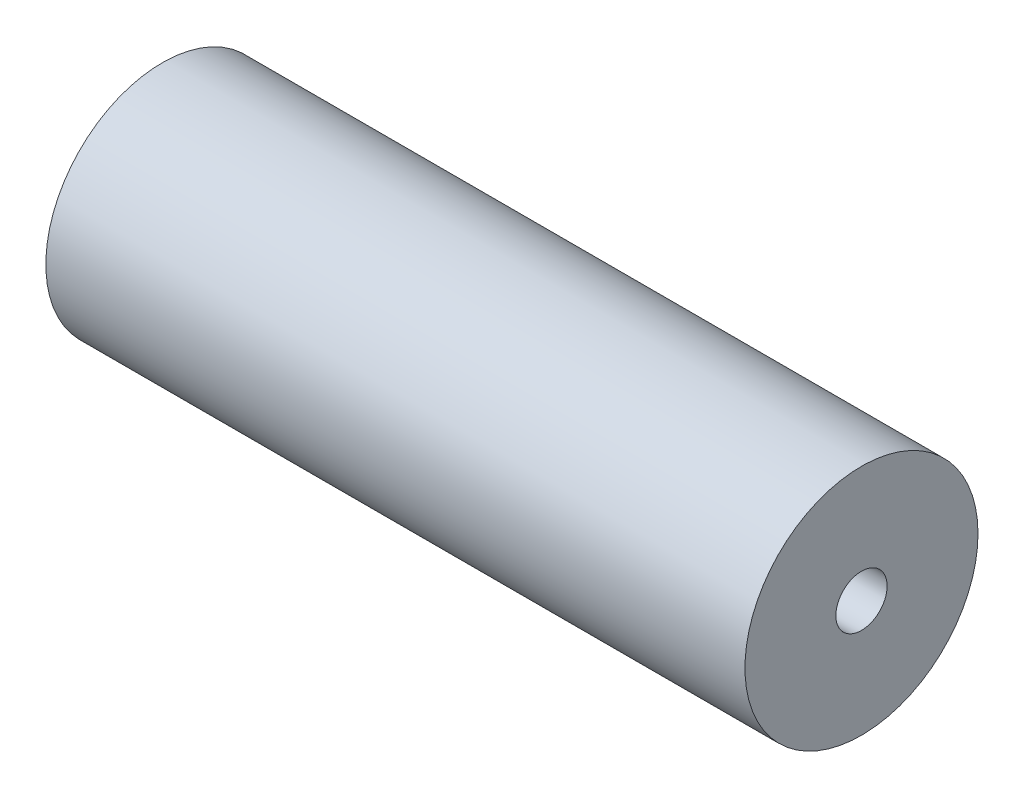
SolidWorks part; units mm, degrees
ref_plane "Plan de face" through (0, 0, 0) normal (0, 0, 1) x (1, 0, 0)
ref_plane "Plan de dessus" through (0, 0, 0) normal (0, 1, 0) x (1, 0, 0)
ref_plane "Plan de droite" through (0, 0, 0) normal (1, 0, 0) x (0, 0, -1)
sketch "Esquisse1" plane through (0, 0, 0) normal (1, 0, 0) x (0, 0, -1)
  circle A0 centre (0, 0) radius 10
extrude "Boss.-Extru.1" add sketch "Esquisse1" along normal blind 60
sketch "Esquisse2" plane through (0, 0, 0) normal (-1, 0, 0) x (0, 0, 1)
  circle A0 centre (0, 0) radius 2.2
extrude "Enlèv. mat.-Extru.1" cut sketch "Esquisse2" against normal blind 60
